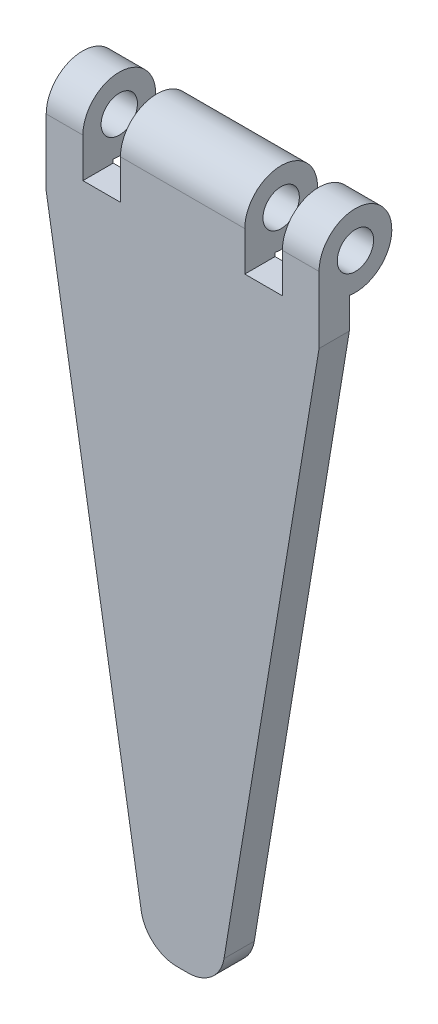
SolidWorks part; units mm, degrees
ref_plane "Alzado" through (0, 0, 0) normal (0, 0, 1) x (1, 0, 0)
ref_plane "Planta" through (0, 0, 0) normal (0, 1, 0) x (1, 0, 0)
ref_plane "Vista lateral" through (0, 0, 0) normal (1, 0, 0) x (0, 0, -1)
sketch "Croquis1" plane through (0, 0, 0) normal (0, 0, 1) x (1, 0, 0)
  line L1 (-22.5, -8.5) -> (22.5, -8.5)
  line L2 (-22.5, -8.5) -> (-22.5, 8.5)
  line L3 (-22.5, 8.5) -> (22.5, 8.5)
  line L4 (22.5, -8.5) -> (22.5, 8.5)
  line L5 (-22.5, -8.5) -> (22.5, 8.5) construction
  line L6 (-22.5, 8.5) -> (22.5, -8.5) construction
  point P0 (0, 0)
  dimension "D1" = 17
  dimension "D2" = 45
extrude "Saliente-Extruir1" add sketch "Croquis1" along normal blind 5
sketch "Croquis2" plane through (22.5, 0, 0) normal (1, 0, 0) x (0, 0, -1)
  line L0 (-5, -8.5) -> (-5, 8.5) construction
  line L1 (-5, 8.5) -> (0, 8.5) construction
  circle A0 centre (1, 2.5) radius 6
  circle A1 centre (1, 2.5) radius 3
  dimension "D1" = 6
  dimension "D2" = 3
  dimension "D3" = 6
  dimension "D4" = 6
extrude "Saliente-Extruir2" add sketch "Croquis2" against normal through all
sketch "Croquis3" plane through (22.5, 0, 0) normal (1, 0, 0) x (0, 0, -1)
  line L0 (-7.9165, 2.5) -> (-5, 2.5)
  line L1 (-5, 2.5) -> (1, 8.5)
  line L2 (1, 8.5) -> (1, 11.4165)
  circle A0 centre (1, 2.5) radius 3
  circle A1 centre (1, 2.5) radius 6
  circle A2 centre (1, 2.5) radius 8.9165
  line M3 (0, 8.4161) -> (0, 8.5)
  line M4 (0, 8.5) -> (-5, 8.5)
  line M5 (-5, 8.5) -> (-5, -8.5)
  line M7 (0, -0.3284) -> (0, 5.3284)
extrude "Cortar-Extruir1" cut sketch "Croquis3" against normal through all contours A1 M3 M4 M5 | A0 M7
sketch "Croquis4" plane through (0, 0, 5) normal (0, 0, 1) x (1, 0, 0)
  line L0 (-22.5, -8.5) -> (22.5, -8.5) construction
  line L1 (-16.45, -8.5) -> (-10.25, -8.5)
  line L2 (-16.45, -8.5) -> (-16.45, 2.5)
  line L3 (-16.45, 2.5) -> (-10.25, 2.5)
  line L4 (-10.25, -8.5) -> (-10.25, 2.5)
  line L5 (-22.5, 2.5) -> (22.5, 2.5) construction
  line L6 (22.5, -8.5) -> (22.5, 2.5) construction
  line L7 (16.45, 2.5) -> (10.25, 2.5)
  line L8 (16.45, 2.5) -> (16.45, -8.5)
  line L9 (16.45, -8.5) -> (10.25, -8.5)
  line L10 (10.25, 2.5) -> (10.25, -8.5)
  line L11 (-22.5, 2.5) -> (-22.5, -8.5) construction
  line L12 (22.5, 8.5) -> (-22.5, 8.5) construction
  line L13 (-16.45, 2.5) -> (-10.25, 2.5)
  line L14 (-16.45, 2.5) -> (-16.45, 8.5)
  line L15 (-16.45, 8.5) -> (-10.25, 8.5)
  line L16 (-10.25, 2.5) -> (-10.25, 8.5)
  line L17 (-16.45, -4) -> (16.45, -4)
  line L18 (16.45, 2.5) -> (10.25, 2.5)
  line L19 (16.45, 2.5) -> (16.45, 8.5)
  line L20 (16.45, 8.5) -> (10.25, 8.5)
  line L21 (10.25, 2.5) -> (10.25, 8.5)
  line M7 (22.5, 2.5) -> (-22.5, 2.5)
  dimension "D1" = 20.5
  dimension "D2" = 6.2
  dimension "D3" = 6.2
  dimension "D4" = 6.05
  dimension "D5" = 6.05
  dimension "D6" = 12.5
extrude "Cortar-Extruir2" cut sketch "Croquis4" against normal through all contours L2 L17 L4 M7 | L16 L15 L14 M7 | L21 L19 L20 M7 | L10 L17 L8 M7
sketch "Croquis5" plane through (0, 0, 0) normal (0, 0, -1) x (-1, 0, 0)
  line L0 (0, -8.5) -> (0, -108.5) construction
  line L1 (22.5, -8.5) -> (-22.5, -8.5) construction
  line L2 (22.5, -8.5) -> (-22.5, -8.5)
  line L3 (6, -108.5) -> (-6, -108.5)
  line L4 (-22.5, -8.5) -> (-6, -108.5)
  line L5 (6, -108.5) -> (22.5, -8.5)
  point P9 (0, -8.5)
  point P12 (0, -108.5)
  dimension "D1" = 12
  dimension "D2" = 100
extrude "Saliente-Extruir3" add sketch "Croquis5" against normal up to surface (5 mm away) up to face at (0, -1.5, 5)
fillet "Redondeo1" radius 5.99 2 edges at (6, -108.5, 2.5) (-6, -108.5, 2.5)
